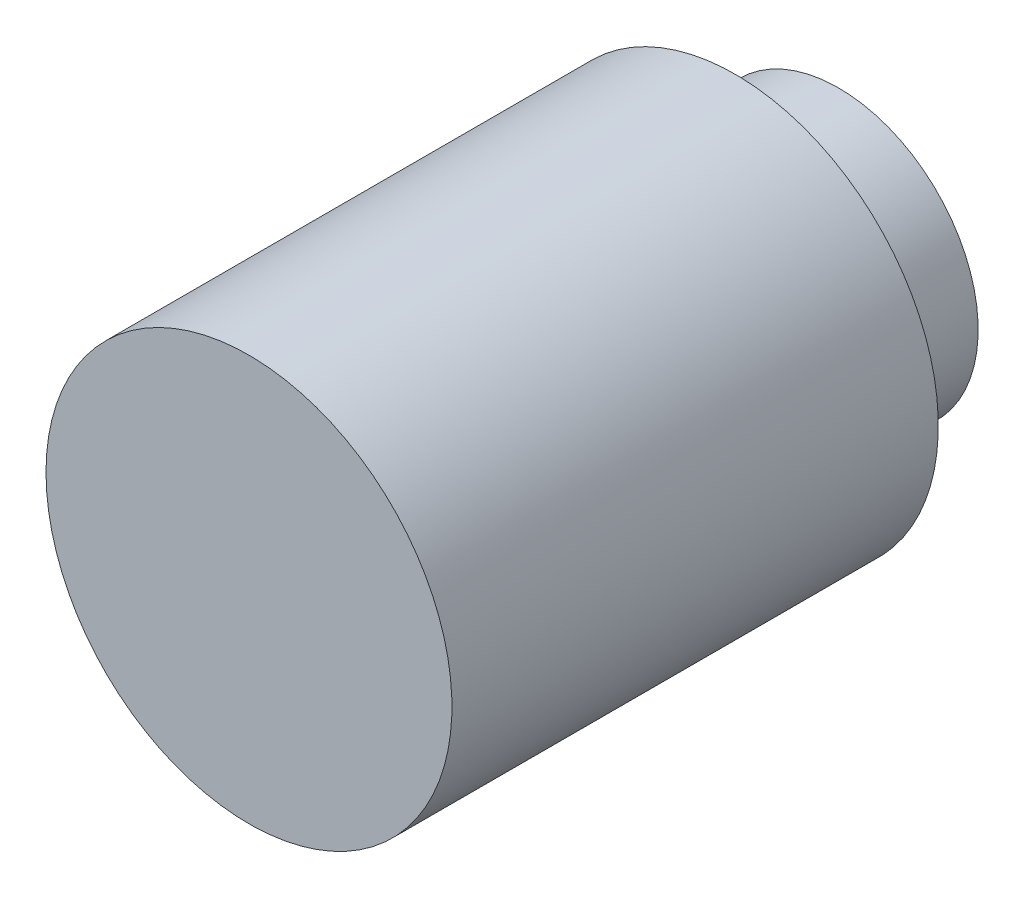
SolidWorks part; units mm, degrees
material "ABS PC"
ref_plane "Front Plane" through (0, 0, 0) normal (0, 0, 1) x (1, 0, 0)
ref_plane "Top Plane" through (0, 0, 0) normal (0, 1, 0) x (1, 0, 0)
ref_plane "Right Plane" through (0, 0, 0) normal (1, 0, 0) x (0, 0, -1)
sketch "Sketch1" plane through (0, 0, 0) normal (0, 1, 0) x (1, 0, 0)
  line L0 (0, 0) -> (6.8898, 0)
  line L1 (-55, 0) -> (55, 0) construction
  line L2 (6.8898, 0) -> (6.8898, 16.51)
  line L3 (6.8898, 16.51) -> (4.7371, 16.51)
  line L4 (4.7371, 16.51) -> (4.7371, 20.0152)
  line L5 (4.7371, 20.0152) -> (0, 20.0152)
  line L6 (0, -55) -> (0, 55) construction
  line L7 (0, 20.0152) -> (0, 0)
  dimension "D1" = 6.8897
  dimension "D2" = 4.7371
  dimension "D3" = 16.51
  dimension "D4" = 3.5052
revolve "Revolve1" add sketch "Sketch1" angle 360 about L7
